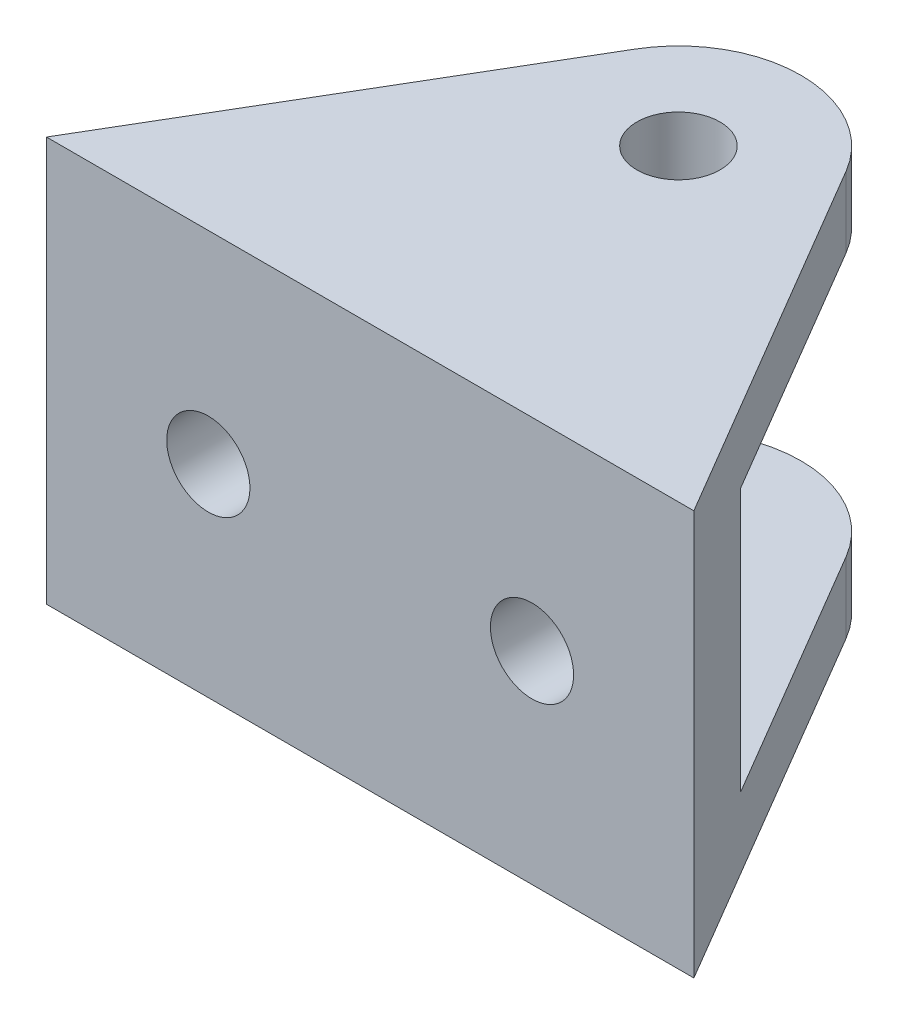
SolidWorks part; units mm, degrees
material "6061-T6 (SS)"
ref_plane "X-Y Datum" through (0, 0, 0) normal (0, 0, 1) x (1, 0, 0)
ref_plane "X-Z Datum" through (0, 0, 0) normal (0, 1, 0) x (1, 0, 0)
ref_plane "Y-Z Datum" through (0, 0, 0) normal (1, 0, 0) x (0, 0, -1)
sketch "Sketch1" plane through (0, 0, 0) normal (1, 0, 0) x (0, 0, -1)
  line L0 (0, 0) -> (0, 31.75)
  line L1 (0, 31.75) -> (43.2881, 31.75)
  line L2 (43.2881, 31.75) -> (43.2881, 26.2001)
  line L3 (43.2881, 26.2001) -> (8.89, 26.2001)
  line L4 (8.89, 26.2001) -> (8.89, 5.5499)
  line L5 (8.89, 5.5499) -> (43.2881, 5.5499)
  line L6 (43.2881, 5.5499) -> (43.2881, 0)
  line L7 (43.2881, 0) -> (0, 0)
  line L8 (30.5881, 31.75) -> (30.5881, 0) construction
  dimension "D1" = 20.6502
  dimension "D2" = 31.75
  dimension "D3" = 12.7
  dimension "D4" = 8.89
extrude "Boss-Extrude1" add sketch "Sketch1" along normal blind 50.8
sketch "Sketch2" plane through (0, 0, -8.89) normal (0, 0, -1) x (-1, 0, 0)
  line L0 (-50.8, 15.875) -> (0, 15.875) construction
  line L1 (-50.8, 5.5499) -> (-50.8, 26.2001) construction
  line L2 (0, 5.5499) -> (0, 26.2001) construction
  line L3 (-25.4, 5.5499) -> (-25.4, 26.2001) construction
  line L4 (-50.8, 5.5499) -> (0, 5.5499) construction
  line L5 (-50.8, 26.2001) -> (0, 26.2001) construction
  point P6 (-38.1, 15.875)
  point P7 (-12.7, 15.875)
  dimension "D1" = 25.4
  dimension "D2" = 12.7
hole_wizard "CBORE for 1/4 Binding Head Machine Screw1" positions "Sketch2" profile "Sketch3" counterbore size "1/4" standard "ANSI Inch" end condition through all
sketch "Sketch3" plane through (12.7, 15.875, -8.89) normal (1, 0, 0) x (0, 1, 0)
  line L0 (0, 0) -> (0, 8.89)
  line L1 (0, 8.89) -> (3.2639, 8.89)
  line L3 (3.2639, 8.89) -> (3.2639, 4.064)
  line L4 (3.2639, 4.064) -> (7.1437, 4.064)
  line L5 (7.1437, 4.064) -> (7.1437, 0)
  line L7 (7.1437, 0) -> (0, 0)
  line L11 (0, -6.35) -> (0, 107.95) construction
  dimension "Thru Hole Dia." = 6.5278
  dimension "Thru Hole Depth" = 8.89
  dimension "C'Bore Dia." = 14.2875
  dimension "C'Bore Depth" = 4.064
sketch "Sketch4" plane through (0, 0, 0) normal (0, -1, 0) x (1, 0, 0)
  line L0 (25.4, 0) -> (25.4, -43.2881) construction
  line L1 (50.8, 0) -> (0, 0) construction
  line L2 (50.8, -43.2881) -> (0, -43.2881) construction
  line L3 (17.1156, -29.0671) -> (0, 0)
  line L4 (33.6844, -29.0671) -> (50.8, 0)
  line L5 (0, 0) -> (0, -43.2881)
  line L6 (0, -43.2881) -> (50.8, -43.2881)
  line L7 (50.8, -43.2881) -> (50.8, 0)
  circle A0 centre (25.4, -24.189) radius 3.2639
  arc A1 (17.1156, -29.0671) -> (33.6844, -29.0671) centre (25.4, -24.189) ccw
  dimension "D1" = 6.5278
  dimension "D2" = 6.35
extrude "Cut-Extrude1" cut sketch "Sketch4" against normal up to surface (31.75 mm away) up to face at (25.4, 31.75, -21.644)
